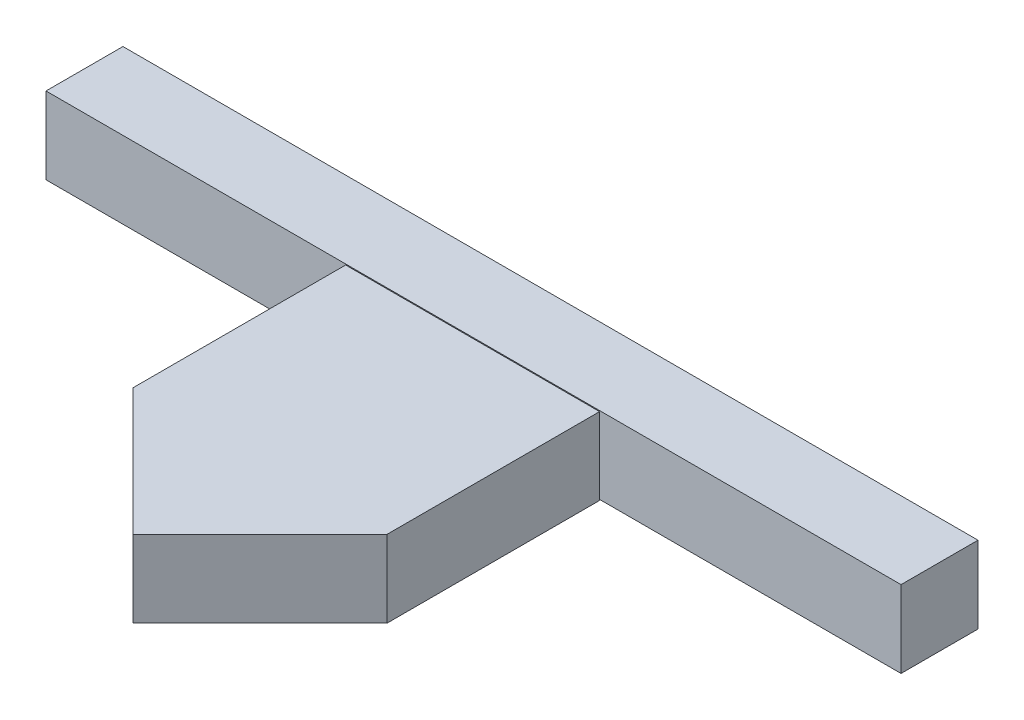
SolidWorks part; units mm, degrees
ref_plane "Front Plane" through (0, 0, 0) normal (0, 0, 1) x (1, 0, 0)
ref_plane "Top Plane" through (0, 0, 0) normal (0, 1, 0) x (1, 0, 0)
ref_plane "Right Plane" through (0, 0, 0) normal (1, 0, 0) x (0, 0, -1)
sketch "Sketch1" plane through (0, 0, 0) normal (0, 1, 0) x (1, 0, 0)
  line L0 (-14.8492, 0) -> (-14.8492, 24.8492)
  line L5 (0, -14.8492) -> (14.8492, 0)
  line L6 (0, -14.8492) -> (-14.8492, 0)
  line L7 (-14.8492, 0) -> (0, 14.8492)
  line L8 (14.8492, 0) -> (0, 14.8492)
  line L9 (0, -14.8492) -> (0, 14.8492) construction
  line L10 (-14.8492, 0) -> (14.8492, 0) construction
  line L11 (-14.8492, 24.8492) -> (14.8492, 24.8492)
  line L12 (14.8492, 24.8492) -> (14.8492, 0)
  line L13 (-50, 24.9573) -> (-50, 144.9573) construction
  line L14 (-50, 33.9573) -> (50, 33.9573)
  line L15 (-50, 33.9573) -> (-50, 24.9573)
  line L16 (-50, 24.9573) -> (50, 24.9573)
  line L17 (50, 33.9573) -> (50, 24.9573)
  point P0 (0, 0)
  dimension "D1" = 21
  dimension "D2" = 21
  dimension "D3" = 29.6985
  dimension "D4" = 29.6985
  dimension "D5" = 21
  dimension "D6" = 10
  dimension "D7" = 9
extrude "Boss-Extrude1" add sketch "Sketch1" along normal blind 9
